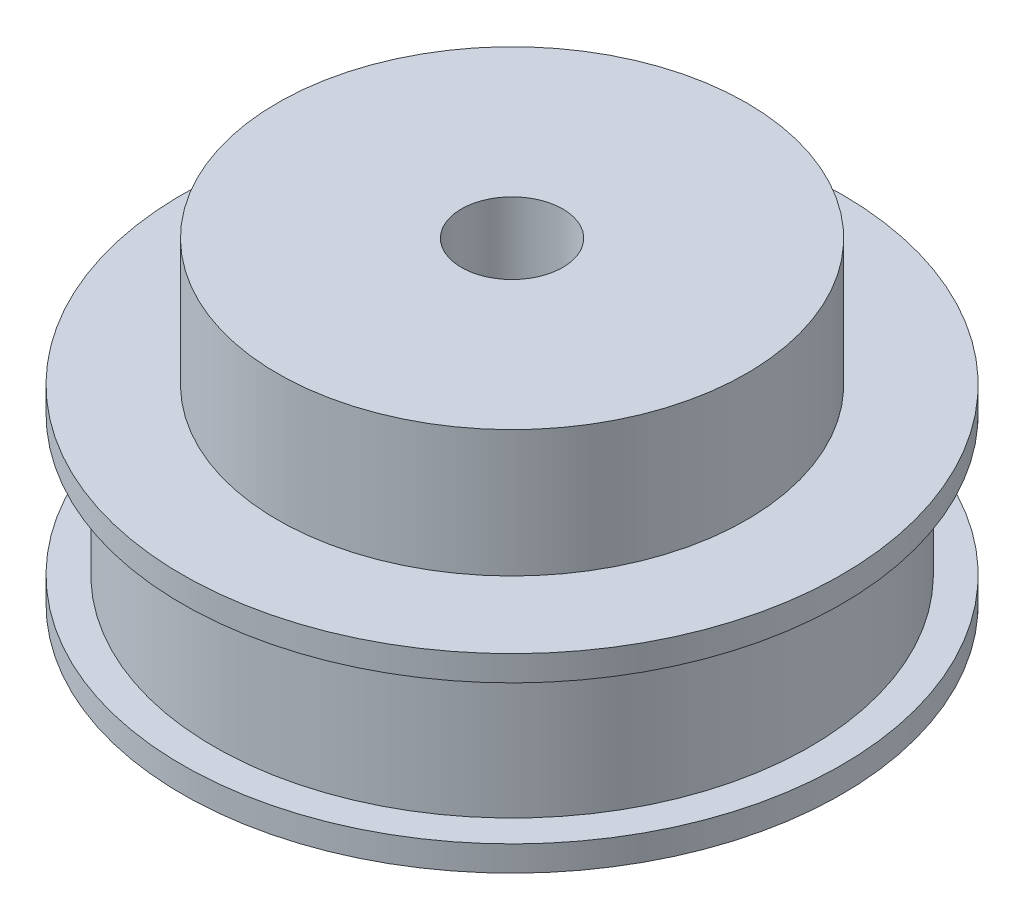
SolidWorks part; units mm, degrees
ref_plane "前视基准面" through (0, 0, 0) normal (0, 0, 1) x (1, 0, 0)
ref_plane "上视基准面" through (0, 0, 0) normal (0, 1, 0) x (1, 0, 0)
ref_plane "右视基准面" through (0, 0, 0) normal (1, 0, 0) x (0, 0, -1)
other "Configuration Table"
sketch "草图2" plane through (0, 0, 0) normal (0, 0, 1) x (1, 0, 0)
  line L5 (0, 0) -> (23092.6172, 0) construction
  line L10 (0, 0) -> (0, 50000) construction
  line L11 (4, 11.6742) -> (4, -13.3258)
  line L12 (4, -13.3258) -> (26, -13.3258)
  line L13 (26, -13.3258) -> (26, -11.3258)
  line L14 (26, -11.3258) -> (23.5, -11.3258)
  line L15 (23.5, -11.3258) -> (23.5, -0.3258)
  line L16 (23.5, -0.3258) -> (26, -0.3258)
  line L17 (26, -0.3258) -> (26, 1.6742)
  line L18 (26, 1.6742) -> (18.5, 1.6742)
  line L19 (18.5, 1.6742) -> (18.5, 11.6742)
  line L20 (18.5, 11.6742) -> (4, 11.6742)
  dimension "D1" = 4
  dimension "D2" = 18.5
  dimension "D3" = 25
  dimension "D4" = 26
  dimension "D5" = 23.5
  dimension "D6" = 26
  dimension "D7" = 23.5
  dimension "D8" = 23.5
  dimension "D9" = 11
  dimension "D10" = 2.5
  dimension "D11" = 2
  dimension "D12" = 2
revolve "旋转1" add sketch "草图2" angle 360 about L10
